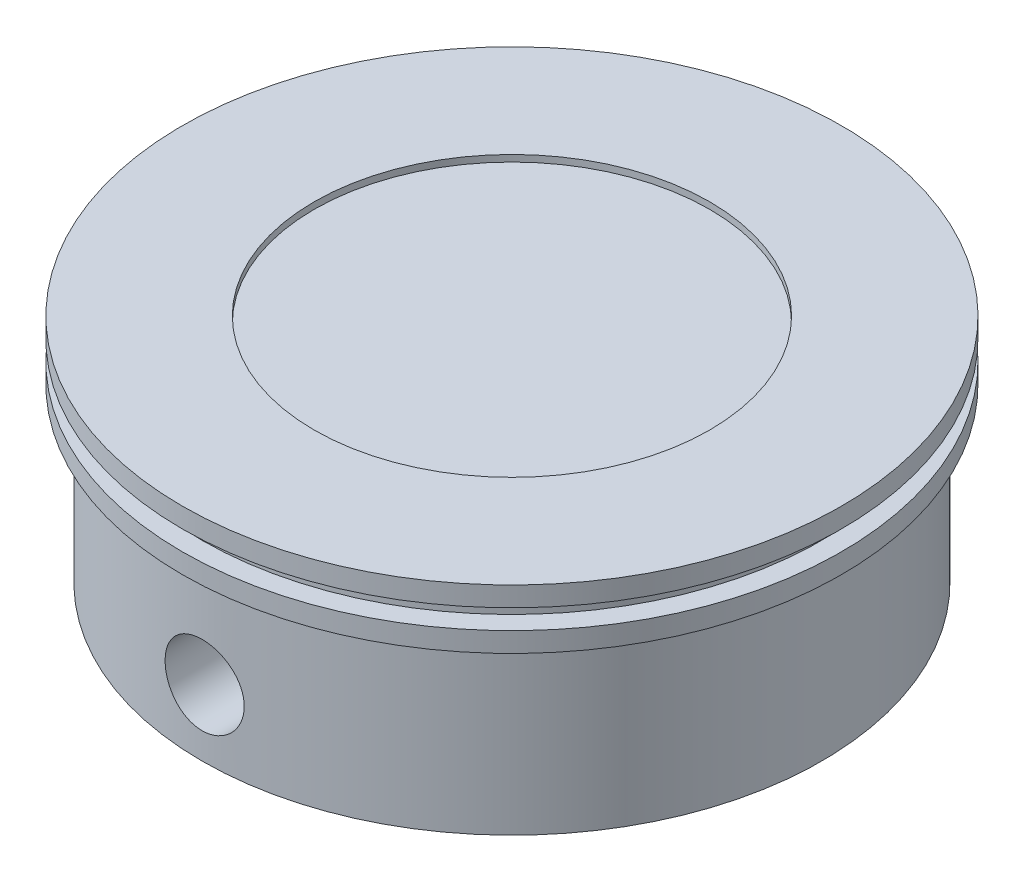
SolidWorks part; units mm, degrees
ref_plane "Front Plane" through (0, 0, 0) normal (0, 0, 1) x (1, 0, 0)
ref_plane "Top Plane" through (0, 0, 0) normal (0, 1, 0) x (1, 0, 0)
ref_plane "Right Plane" through (0, 0, 0) normal (1, 0, 0) x (0, 0, -1)
sketch "Sketch2" plane through (0, 0, 0) normal (0, 0, 1) x (1, 0, 0)
  line L0 (0, 20.9352) -> (0, -14.0648) construction
  line L1 (0, -14.0648) -> (47, -14.0648)
  line L2 (47, -14.0648) -> (47, 11.9352)
  line L3 (47, 11.9352) -> (50, 11.9352)
  line L4 (50, 11.9352) -> (50, 14.9352)
  line L5 (50, 14.9352) -> (47, 14.9352)
  line L6 (47, 14.9352) -> (47, 17.9352)
  line L7 (47, 17.9352) -> (50, 17.9352)
  line L8 (50, 17.9352) -> (50, 20.9352)
  line L9 (50, 20.9352) -> (0, 20.9352)
  line L10 (0, 20.9352) -> (0, -14.0648)
  dimension "D1" = 35
  dimension "D2" = 47
  dimension "D3" = 26
  dimension "D4" = 3
  dimension "D5" = 3
  dimension "D6" = 3
  dimension "D7" = 3
revolve "Revolve1" add sketch "Sketch2" angle 360 about L0
sketch "Sketch3" plane through (0, -14.0648, 0) normal (0, -1, 0) x (1, 0, 0)
  circle A0 centre (0, 0) radius 30
  dimension "D1" = 60
extrude "Cut-Extrude1" cut sketch "Sketch3" against normal blind 27
ref_plane "Plane1" through (0, 0, 47) normal (0, 0, 1) x (1, 0, 0)
sketch "Sketch4" plane through (0, 0, 47) normal (0, 0, 1) x (1, 0, 0)
  line L0 (-47, -14.0648) -> (47, -14.0648) construction
  circle A0 centre (0, -4.0648) radius 6
  dimension "D1" = 12
  dimension "D2" = 10
extrude "Cut-Extrude2" cut sketch "Sketch4" against normal through all
sketch "Sketch5" plane through (0, 20.9352, 0) normal (0, 1, 0) x (1, 0, 0)
  circle A0 centre (0, 0) radius 30
  dimension "D1" = 60
extrude "Cut-Extrude3" cut sketch "Sketch5" against normal blind 1
